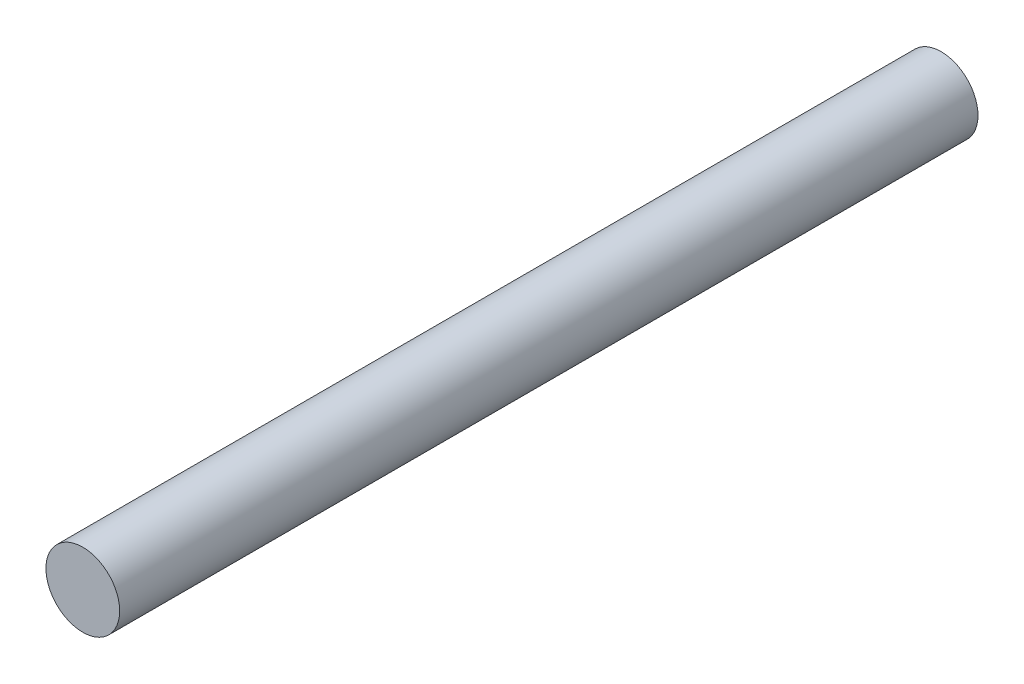
SolidWorks part; units mm, degrees
ref_plane "Plan de face" through (0, 0, 0) normal (0, 0, 1) x (1, 0, 0)
ref_plane "Plan de dessus" through (0, 0, 0) normal (0, 1, 0) x (1, 0, 0)
ref_plane "Plan de droite" through (0, 0, 0) normal (1, 0, 0) x (0, 0, -1)
sketch "Esquisse1" plane through (0, 0, 0) normal (0, 0, 1) x (1, 0, 0)
  circle A0 centre (0, 0) radius 3
  dimension "D1" = 6
extrude "Boss.-Extru.1" add sketch "Esquisse1" along normal blind 69.85
